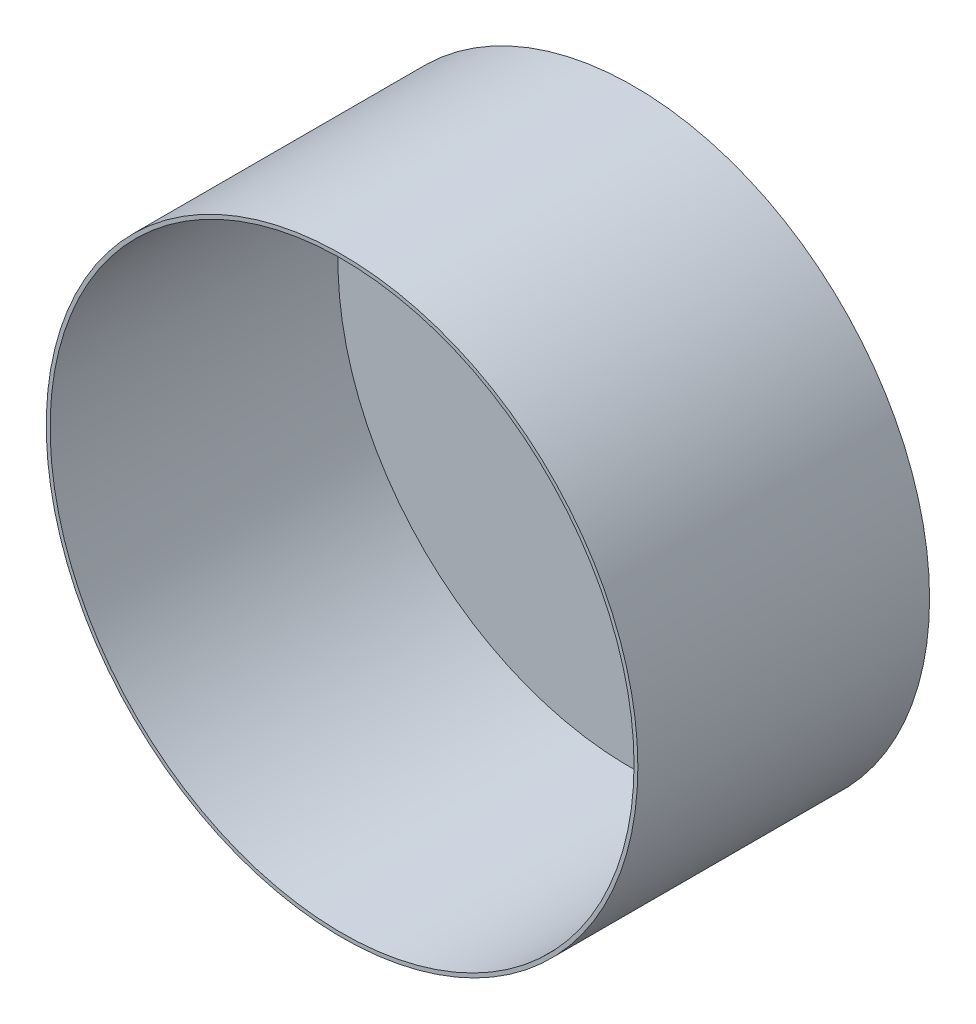
SolidWorks part; units mm, degrees
ref_plane "Front Plane" through (0, 0, 0) normal (0, 0, 1) x (1, 0, 0)
ref_plane "Top Plane" through (0, 0, 0) normal (0, 1, 0) x (1, 0, 0)
ref_plane "Right Plane" through (0, 0, 0) normal (1, 0, 0) x (0, 0, -1)
sketch "Sketch2" plane through (0, 0, 0) normal (0, 0, 1) x (1, 0, 0)
  circle A0 centre (0, 0) radius 38.535
  dimension "D1" = 77.07
extrude "Boss-Extrude1" add sketch "Sketch2" along normal blind 38
sketch "Sketch3" plane through (0, 0, 38) normal (0, 0, 1) x (1, 0, 0)
  circle A0 centre (0, 0) radius 38.035
  dimension "D1" = 76.07
extrude "Cut-Extrude1" cut sketch "Sketch3" against normal blind 37.5
